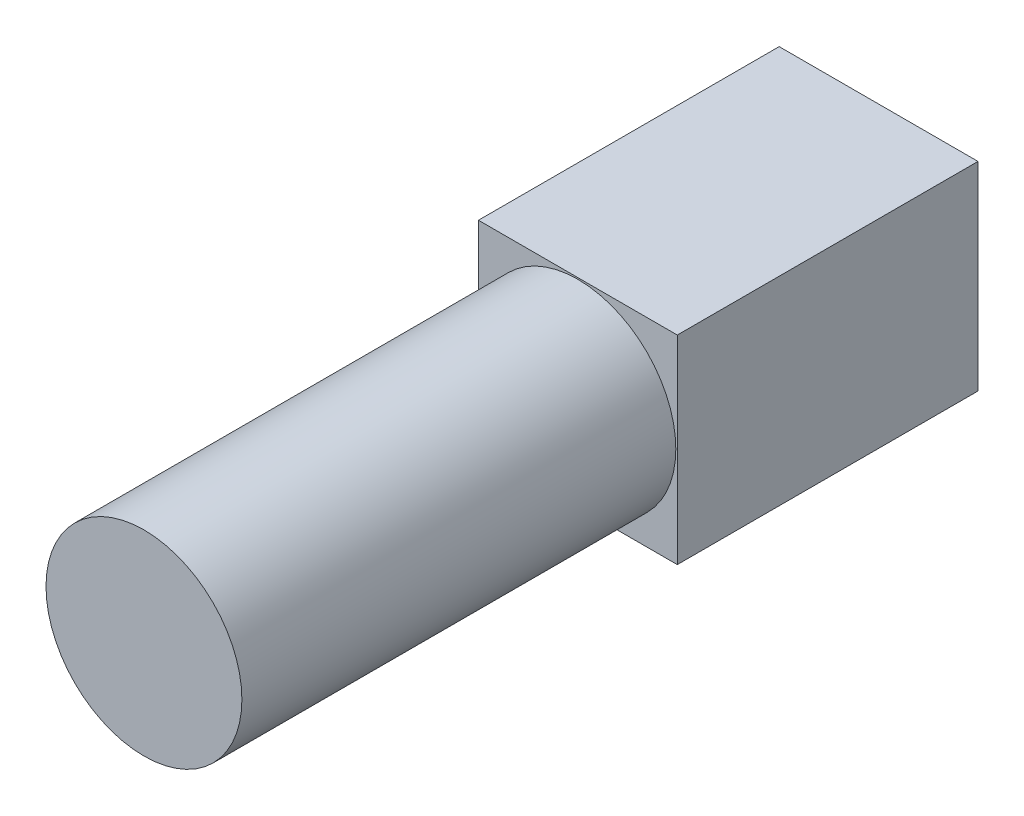
SolidWorks part; units mm, degrees
ref_plane "Top Plane" through (0, 0, 0) normal (0, 0, 1) x (1, 0, 0)
ref_plane "Front Plane" through (0, 0, 0) normal (0, 1, 0) x (1, 0, 0)
ref_plane "Right Plane" through (0, 0, 0) normal (1, 0, 0) x (0, 0, -1)
sketch "Sketch1" plane through (0, 0, 0) normal (0, 0, 1) x (1, 0, 0)
  line L1 (-4.06, -4.06) -> (4.06, -4.06)
  line L2 (-4.06, -4.06) -> (-4.06, 4.06)
  line L3 (-4.06, 4.06) -> (4.06, 4.06)
  line L4 (4.06, -4.06) -> (4.06, 4.06)
  line L5 (-4.06, -4.06) -> (4.06, 4.06) construction
  line L6 (-4.06, 4.06) -> (4.06, -4.06) construction
  point P0 (0, 0)
  dimension "D1" = 8.12
  dimension "D2" = 8.12
extrude "Boss-Extrude1" add sketch "Sketch1" along normal blind 12.28
sketch "Sketch2" plane through (0, 0, 0) normal (0, 0, 1) x (1, 0, 0)
  circle A0 centre (0, 0) radius 4
  dimension "D1" = 8
extrude "Boss-Extrude2" add sketch "Sketch2" along normal blind 30
